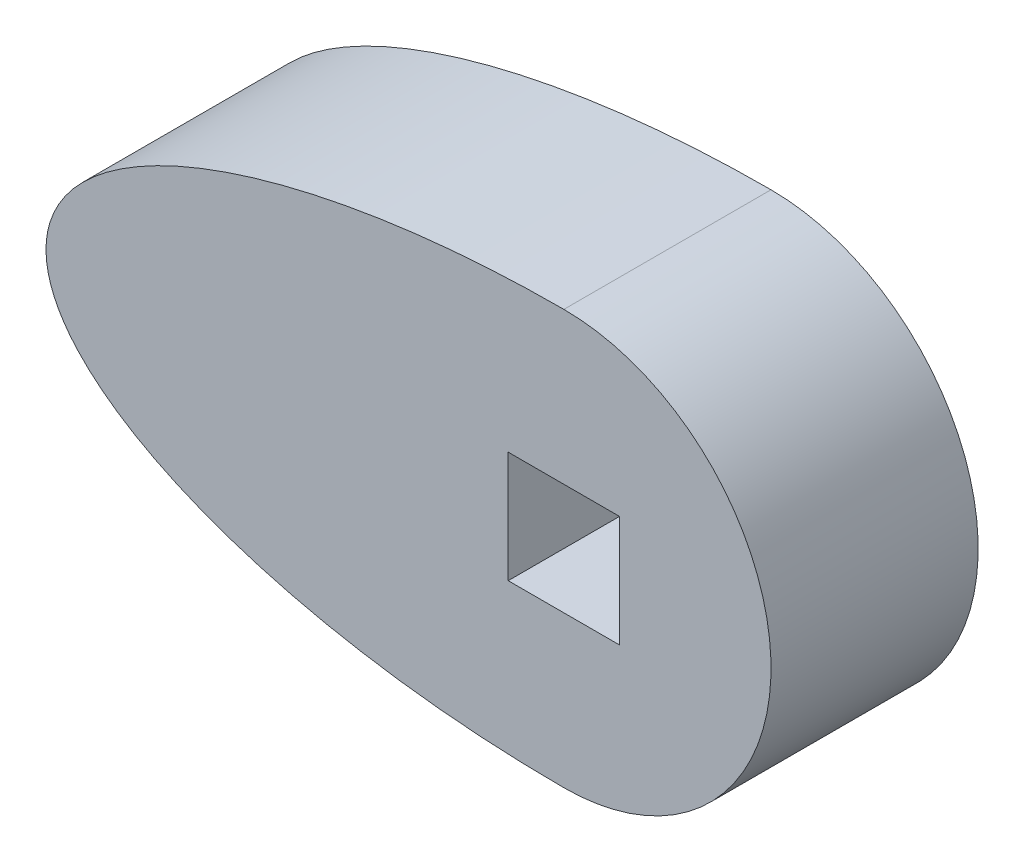
SolidWorks part; units mm, degrees
ref_plane "Front Plane" through (0, 0, 0) normal (0, 0, 1) x (1, 0, 0)
ref_plane "Top Plane" through (0, 0, 0) normal (0, 1, 0) x (1, 0, 0)
ref_plane "Right Plane" through (0, 0, 0) normal (1, 0, 0) x (0, 0, -1)
sketch "Sketch4" plane through (0, 0, 0) normal (0, 0, 1) x (1, 0, 0)
  line L0 (0, 0) -> (0, 10) construction
  line L1 (0, 0) -> (-25, 0) construction
  dimension "D1" = 10
  dimension "D2" = 25
sketch "L" plane through (0, 0, 0) normal (0, 0, 1) x (1, 0, 0)
  line L0 (0, 0) -> (0, -10) construction
  line L1 (0, 0) -> (25, 0) construction
  line L2 (0, 0) -> (0, 10) construction
  line L3 (0, 0) -> (-28.8314, 0) construction
  spline S1 degree 4 poles (2.2591, 8.364) (2.1926, 8.4214) (2.0587, 8.5352) (1.8546, 8.7034) (1.5802, 8.9204) (1.2974, 9.1337) (1.0216, 9.3339) (0.7194, 9.5414) (0.4674, 9.7102) (0.1096, 9.9341) (-0.0654, 10.0403) (-0.3706, 10.2188) (-0.6083, 10.3515) (-0.824, 10.4676) (-1.0114, 10.5652) (-1.1995, 10.6607) (-1.3883, 10.7539) (-1.6102, 10.8597) (-1.9296, 11.0058) (-2.3165, 11.1729) (-2.773, 11.3558) (-3.565, 11.6445) (-4.7747, 12.015) (-6.4247, 12.3753) (-8.5252, 12.5961) (-10.7776, 12.569) (-12.8586, 12.306) (-14.9014, 11.8356) (-16.8881, 11.1667) (-18.8017, 10.3091) (-20.7499, 9.1804) (-22.5734, 7.8599) (-24.0462, 6.5519) (-25.2125, 5.3327) (-26.0266, 4.3648) (-26.5431, 3.6986) (-26.9559, 3.1302) (-27.2753, 2.6678) (-27.5837, 2.1982) (-27.844, 1.7808) (-28.06, 1.4193) (-28.2356, 1.1148) (-28.3737, 0.8687) (-28.5054, 0.628) (-28.6406, 0.3732) (-28.8052, 0.0536) (-28.9094, -0.1553) (-29.1337, -0.6169) (-29.2818, -0.9447) (-29.4691, -1.367) (-29.6265, -1.746) (-29.7889, -2.1515) (-29.9383, -2.5471) (-30.0479, -2.8511) (-30.1178, -3.0528) (-30.1521, -3.1538) knots 0 0 0 0 0 0.008697 0.017393 0.02609 0.034786 0.043356 0.051926 0.060495 0.069065 0.076013 0.082961 0.089909 0.096858 0.100332 0.103806 0.110754 0.117702 0.12465 0.138547 0.152443 0.16634 0.208029 0.263615 0.3192 0.374786 0.430372 0.470684 0.52627 0.581855 0.637441 0.693027 0.748612 0.776405 0.804198 0.818095 0.831991 0.845887 0.859784 0.87368 0.880628 0.887577 0.894525 0.901473 0.908421 0.91537 0.925948 0.936527 0.947106 0.957685 0.968264 0.978842 0.989421 1 1 1 1 1 construction
  spline S2 degree 4 poles (0, 10) (-0.0509, 10.0307) (-0.1543, 10.0923) (-0.3706, 10.2188) (-0.6083, 10.3515) (-0.824, 10.4676) (-1.0114, 10.5652) (-1.1995, 10.6607) (-1.3883, 10.7539) (-1.6102, 10.8597) (-1.9296, 11.0058) (-2.3165, 11.1729) (-2.773, 11.3558) (-3.565, 11.6445) (-4.7747, 12.015) (-6.4247, 12.3753) (-8.5252, 12.5961) (-10.7776, 12.569) (-12.8586, 12.306) (-14.9014, 11.8356) (-16.8881, 11.1667) (-18.8017, 10.3091) (-20.7499, 9.1804) (-22.5734, 7.8599) (-24.0462, 6.5519) (-25.2125, 5.3327) (-26.0266, 4.3648) (-26.5431, 3.6986) (-26.9559, 3.1302) (-27.2753, 2.6678) (-27.5837, 2.1982) (-27.844, 1.7808) (-28.06, 1.4193) (-28.2356, 1.1148) (-28.3737, 0.8687) (-28.5054, 0.628) (-28.6406, 0.3732) (-28.7498, 0.1612) (-28.8047, 0.0531) (-28.8314, 0) knots 0.069065 0.069065 0.069065 0.069065 0.069065 0.076013 0.082961 0.089909 0.096858 0.100332 0.103806 0.110754 0.117702 0.12465 0.138547 0.152443 0.16634 0.208029 0.263615 0.3192 0.374786 0.430372 0.470684 0.52627 0.581855 0.637441 0.693027 0.748612 0.776405 0.804198 0.818095 0.831991 0.845887 0.859784 0.87368 0.880628 0.887577 0.894525 0.901473 0.908421 0.91537 0.91537 0.91537 0.91537 0.91537
  dimension "D1" = 10
  dimension "D2" = 25
sketch "Sketch2" plane through (0, 0, 0) normal (0, 0, 1) x (1, 0, 0)
  line L0 (0, 10) -> (10, 0)
  line L1 (10, 0) -> (-28.8314, 0)
  spline S0 degree 4 poles (1711.3489, -1024.1766) (-44.469, 36.4589) (3.6301, 7.7183) (0.663, 9.6418) (-0.6083, 10.3515) (-0.824, 10.4676) (-1.0114, 10.5652) (-1.1995, 10.6607) (-1.3883, 10.7539) (-1.6102, 10.8597) (-1.9296, 11.0058) (-2.3165, 11.1729) (-2.773, 11.3558) (-3.565, 11.6445) (-4.7747, 12.015) (-6.4247, 12.3753) (-8.5252, 12.5961) (-10.7776, 12.569) (-12.8586, 12.306) (-14.9014, 11.8356) (-16.8881, 11.1667) (-18.8017, 10.3091) (-20.7499, 9.1804) (-22.5734, 7.8599) (-24.0462, 6.5519) (-25.2125, 5.3327) (-26.0266, 4.3648) (-26.5431, 3.6986) (-26.9559, 3.1302) (-27.2753, 2.6678) (-27.5837, 2.1982) (-27.844, 1.7808) (-28.06, 1.4193) (-28.2356, 1.1148) (-28.3737, 0.8687) (-28.5054, 0.628) (-29.2767, -0.8255) (-30.4266, -3.3205) (-7.8225, 41.2196) (-925.9153, -1786.783) knots -0.05179 -0.05179 -0.05179 -0.05179 -0.05179 0.076013 0.082961 0.089909 0.096858 0.100332 0.103806 0.110754 0.117702 0.12465 0.138547 0.152443 0.16634 0.208029 0.263615 0.3192 0.374786 0.430372 0.470684 0.52627 0.581855 0.637441 0.693027 0.748612 0.776405 0.804198 0.818095 0.831991 0.845887 0.859784 0.87368 0.880628 0.887577 0.894525 0.901473 0.908421 1.046125 1.046125 1.046125 1.046125 1.046125 only from (0, 10) to (-28.8314, 0) construction
  spline S1 degree 4 poles (0, 10) (-0.0509, 10.0307) (-0.1543, 10.0923) (-0.3706, 10.2188) (-0.6083, 10.3515) (-0.824, 10.4676) (-1.0114, 10.5652) (-1.1995, 10.6607) (-1.3883, 10.7539) (-1.6102, 10.8597) (-1.9296, 11.0058) (-2.3165, 11.1729) (-2.773, 11.3558) (-3.565, 11.6445) (-4.7747, 12.015) (-6.4247, 12.3753) (-8.5252, 12.5961) (-10.7776, 12.569) (-12.8586, 12.306) (-14.9014, 11.8356) (-16.8881, 11.1667) (-18.8017, 10.3091) (-20.7499, 9.1804) (-22.5734, 7.8599) (-24.0462, 6.5519) (-25.2125, 5.3327) (-26.0266, 4.3648) (-26.5431, 3.6986) (-26.9559, 3.1302) (-27.2753, 2.6678) (-27.5837, 2.1982) (-27.844, 1.7808) (-28.06, 1.4193) (-28.2356, 1.1148) (-28.3737, 0.8687) (-28.5054, 0.628) (-28.6406, 0.3732) (-28.7498, 0.1612) (-28.8047, 0.0531) (-28.8314, 0) knots 0.069065 0.069065 0.069065 0.069065 0.069065 0.076013 0.082961 0.089909 0.096858 0.100332 0.103806 0.110754 0.117702 0.12465 0.138547 0.152443 0.16634 0.208029 0.263615 0.3192 0.374786 0.430372 0.470684 0.52627 0.581855 0.637441 0.693027 0.748612 0.776405 0.804198 0.818095 0.831991 0.845887 0.859784 0.87368 0.880628 0.887577 0.894525 0.901473 0.908421 0.91537 0.91537 0.91537 0.91537 0.91537
  dimension "D1" = 10
extrude "Boss-Extrude1" [suppressed] add sketch "Sketch2" against normal blind 10
mirror "Mirror1" [suppressed]
fillet "Fillet1" [suppressed] radius 5
sketch "Sketch5" plane through (0, 0, 0) normal (0, 0, 1) x (1, 0, 0)
  line L0 (0, 10) -> (0, 0) construction
  line L1 (0, 0) -> (-25, 0)
  line L2 (0, 0) -> (10, 0)
  arc A0 (10, 0) -> (0, 10) centre (0, 0) ccw
  ellipse E0 centre (0, 0) end of major axis (-25, 0) minor radius 10 (0, 10) -> (-25, 0) ccw
extrude "Boss-Extrude5" add sketch "Sketch5" against normal blind 10 contours E0 L1 L2 A0
mirror "Mirror2" about plane through (0, 0, -10) normal (0, -1, 0) of bodies 107 108
sketch "Sketch3" plane through (0, 0, 0) normal (0, 0, 1) x (1, 0, 0)
  line L1 (2.687, -2.687) -> (-2.687, -2.687)
  line L2 (2.687, -2.687) -> (2.687, 2.687)
  line L3 (2.687, 2.687) -> (-2.687, 2.687)
  line L4 (-2.687, -2.687) -> (-2.687, 2.687)
  line L5 (2.687, -2.687) -> (-2.687, 2.687) construction
  line L6 (2.687, 2.687) -> (-2.687, -2.687) construction
  circle A0 centre (0, 0) radius 3.8 construction
  dimension "D1" = 7.6
extrude "Cut-Extrude2" cut sketch "Sketch3" against normal through all contours L3 L4 L1 L2
equation "\"r1\"= 10"
equation "\"r2\"= 25"
equation "\"D1@Sketch4\"=\"r1\""
equation "\"D2@Sketch4\"=\"r2\""
equation "\"shaft\"= 7.6"
equation "\"D1@Sketch3\"=\"shaft\""
equation "\"t\"= 10"
equation "\"D1@Boss-Extrude1\"=\"t\""
equation "\"D1@Boss-Extrude5\"=\"t\""
equation "\"D1@L\" = \"r1\""
equation "\"D2@L\" = \"r2\""
